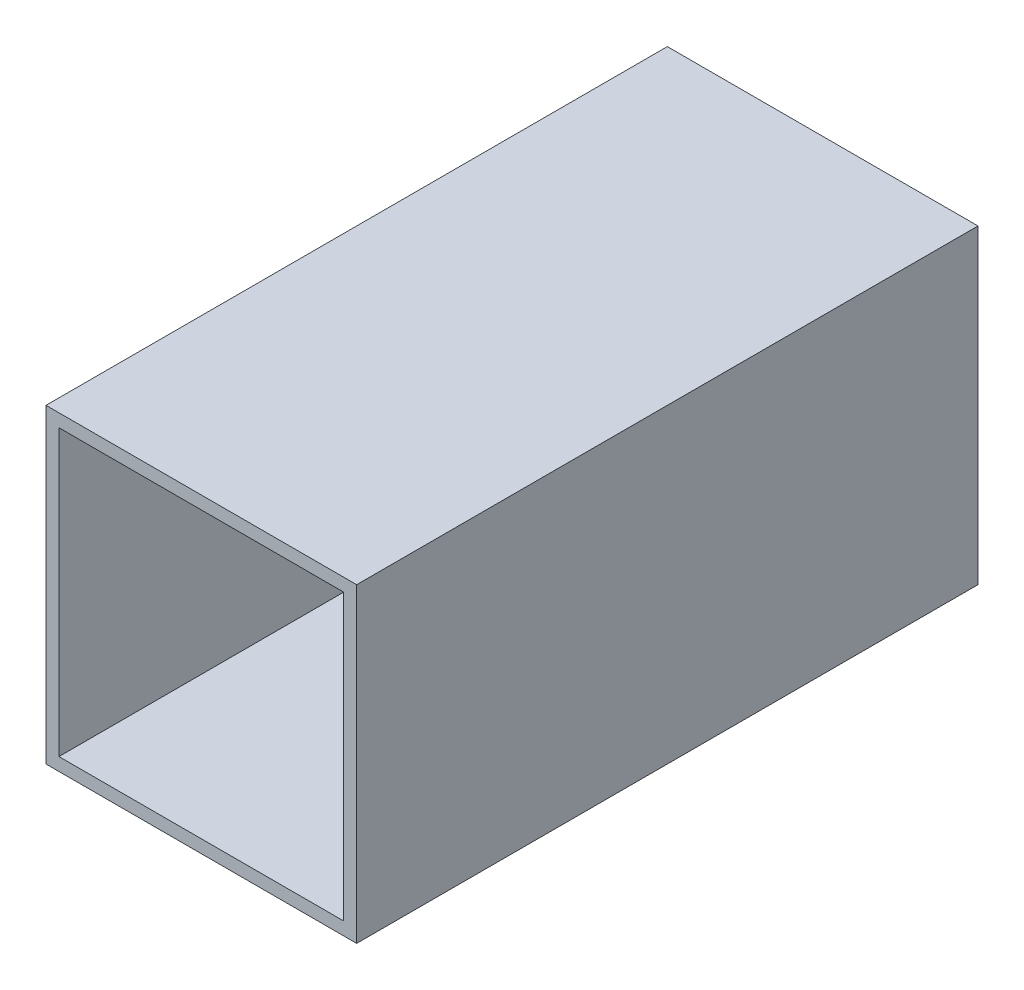
SolidWorks part; units mm, degrees
ref_plane "Front Plane" through (0, 0, 0) normal (0, 0, 1) x (1, 0, 0)
ref_plane "Top Plane" through (0, 0, 0) normal (0, 1, 0) x (1, 0, 0)
ref_plane "Right Plane" through (0, 0, 0) normal (1, 0, 0) x (0, 0, -1)
sketch "Sketch1" plane through (0, 0, 0) normal (0, 0, 1) x (1, 0, 0)
  line L0 (-34.925, 34.925) -> (34.925, 34.925)
  line L1 (-38.1, -38.1) -> (38.1, -38.1)
  line L2 (-38.1, -38.1) -> (-38.1, 38.1)
  line L3 (-38.1, 38.1) -> (38.1, 38.1)
  line L4 (38.1, -38.1) -> (38.1, 38.1)
  line L5 (-38.1, -38.1) -> (38.1, 38.1) construction
  line L6 (-38.1, 38.1) -> (38.1, -38.1) construction
  line L7 (34.925, -34.925) -> (34.925, 34.925)
  line L8 (-34.925, -34.925) -> (34.925, -34.925)
  line L9 (-34.925, -34.925) -> (-34.925, 34.925)
  point P0 (0, 0)
  dimension "D1" = 76.2
  dimension "D2" = 3.175
extrude "Boss-Extrude1" add sketch "Sketch1" along normal mid plane 152.4
